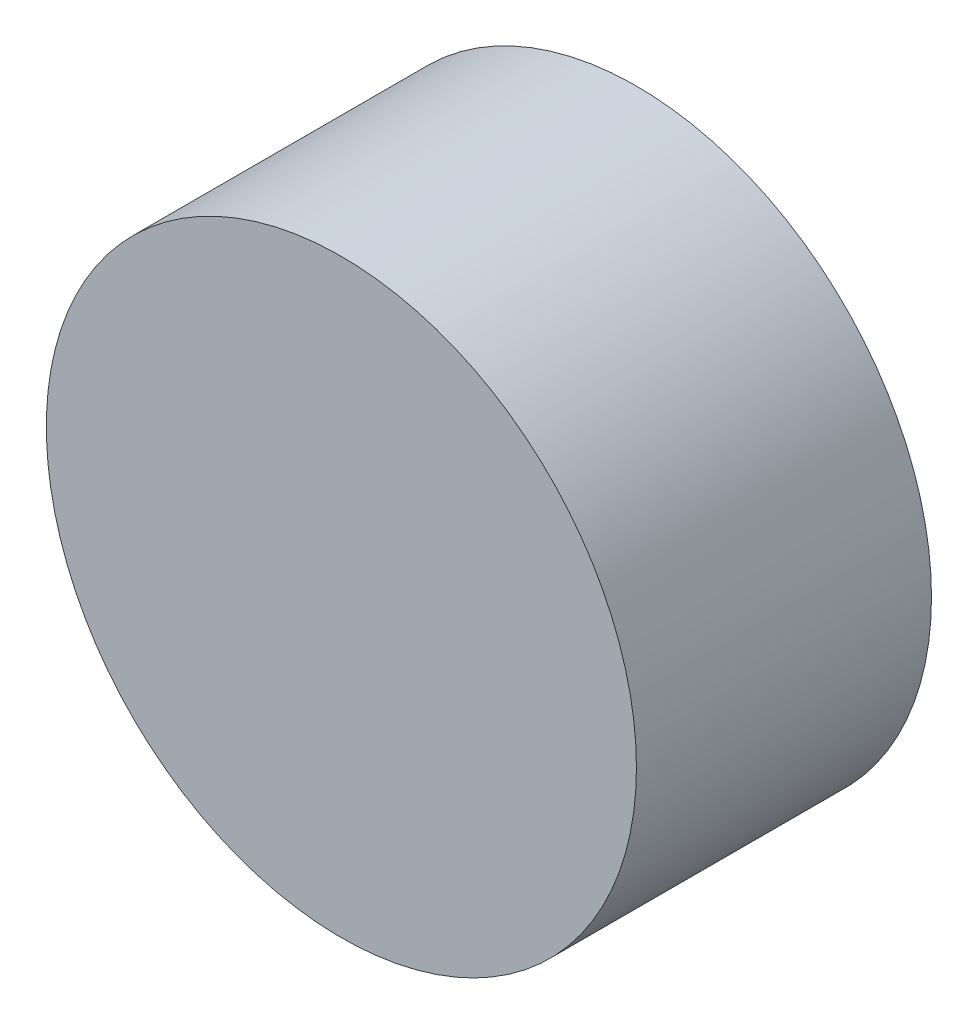
SolidWorks part; units mm, degrees
ref_plane "Front Plane" through (0, 0, 0) normal (0, 0, 1) x (1, 0, 0)
ref_plane "Top Plane" through (0, 0, 0) normal (0, 1, 0) x (1, 0, 0)
ref_plane "Right Plane" through (0, 0, 0) normal (1, 0, 0) x (0, 0, -1)
sketch "Sketch1" plane through (0, 0, 0) normal (0, 0, 1) x (1, 0, 0)
  circle A0 centre (0, 0) radius 3
extrude "Magnet" add sketch "Sketch1" along normal blind 3
